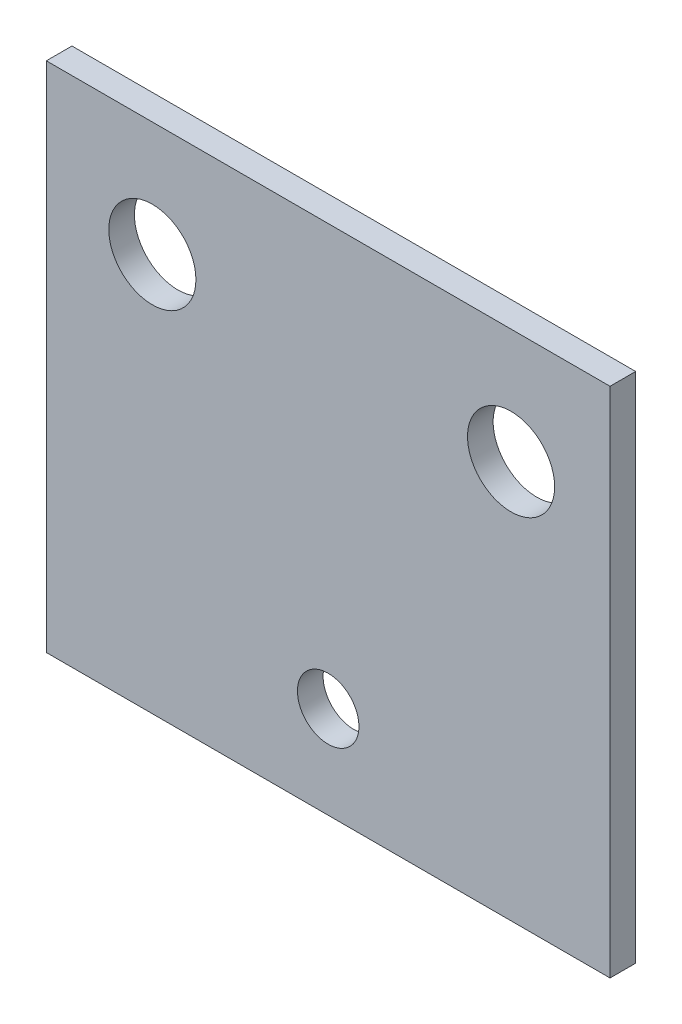
SolidWorks part; units mm, degrees
ref_plane "Alzado" through (0, 0, 0) normal (0, 0, 1) x (1, 0, 0)
ref_plane "Planta" through (0, 0, 0) normal (0, 1, 0) x (1, 0, 0)
ref_plane "Vista lateral" through (0, 0, 0) normal (1, 0, 0) x (0, 0, -1)
sketch "Croquis1" plane through (0, 0, 0) normal (0, 0, 1) x (1, 0, 0)
  line L1 (55, -50) -> (-55, -50)
  line L2 (55, -50) -> (55, 50)
  line L3 (55, 50) -> (-55, 50)
  line L4 (-55, -50) -> (-55, 50)
  line L5 (55, -50) -> (-55, 50) construction
  line L6 (55, 50) -> (-55, -50) construction
  circle A0 centre (0, -31.9997) radius 6
  circle A1 centre (35.6877, 27.6041) radius 8.5
  circle A2 centre (-34.3123, 27.6041) radius 8.5
  point P0 (0, 0)
  point P12 (0, -31.826)
  point P13 (-23.9306, 26.5896)
  point P14 (0, 0)
  point P15 (24.989, 27.7655)
  point P16 (0, 0)
  point P17 (0, 0)
  point P18 (-37.2343, 28.3799)
  point P19 (35.6877, 27.6041)
  dimension "D3" = 70
  dimension "D1" = 100
  dimension "D2" = 110
  dimension "D4" = 59.6037
extrude "Saliente-Extruir1" add sketch "Croquis1" along normal blind 5
